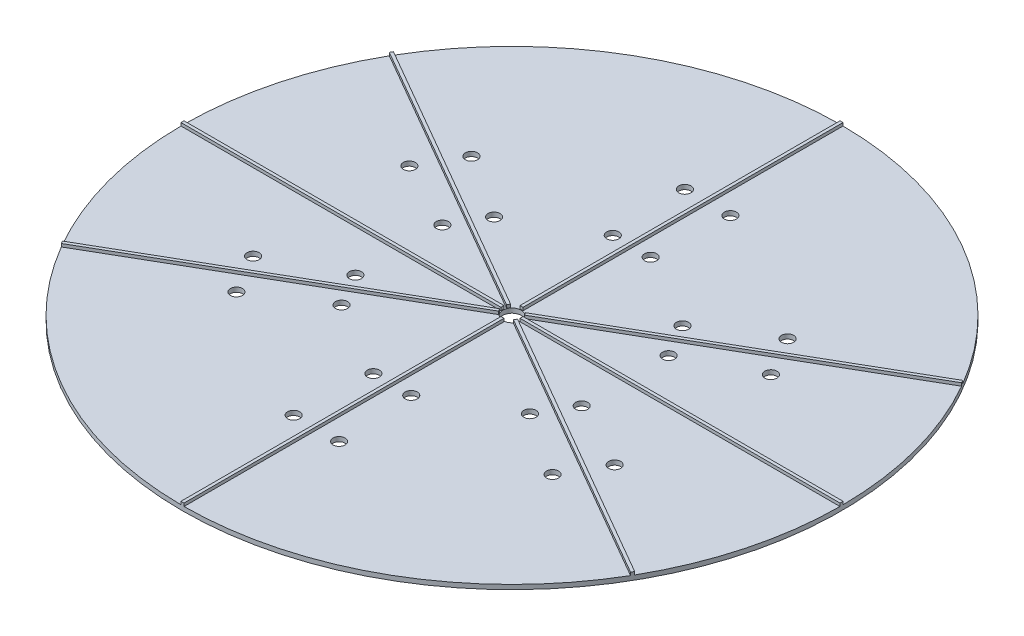
SolidWorks part; units mm, degrees
ref_plane "Front Plane" through (0, 0, 0) normal (0, 0, 1) x (1, 0, 0)
ref_plane "Top Plane" through (0, 0, 0) normal (0, 1, 0) x (1, 0, 0)
ref_plane "Right Plane" through (0, 0, 0) normal (1, 0, 0) x (0, 0, -1)
sketch "Sketch1" plane through (0, 0, 0) normal (0, 1, 0) x (1, 0, 0)
  line L0 (0, -1000) -> (0, 49000) construction
  line L1 (-1000, 0) -> (49000, 0) construction
  line L2 (0, 0) -> (-188.3605, -108.75) construction
  line L3 (0, 0) -> (188.3605, -108.75) construction
  circle A0 centre (0, 0) radius 217.5
  circle A1 centre (0, 0) radius 80 construction
  circle A2 centre (-12.5, 79.0174) radius 4
  circle A3 centre (12.5, 79.0174) radius 4
  circle A8 centre (62.1811, 50.334) radius 4
  circle A9 centre (74.6811, 28.6834) radius 4
  circle A10 centre (74.6811, -28.6834) radius 4
  circle A11 centre (62.1811, -50.334) radius 4
  circle A12 centre (12.5, -79.0174) radius 4
  circle A13 centre (-12.5, -79.0174) radius 4
  circle A14 centre (-62.1811, -50.334) radius 4
  circle A15 centre (-74.6811, -28.6834) radius 4
  circle A16 centre (-74.6811, 28.6834) radius 4
  circle A17 centre (-62.1811, 50.334) radius 4
  circle A18 centre (0, 0) radius 130 construction
  circle A19 centre (15, 129.1317) radius 4
  circle A20 centre (-15, 129.1317) radius 4
  circle A21 centre (104.3313, 77.5562) radius 4
  circle A22 centre (119.3313, 51.5755) radius 4
  circle A23 centre (119.3313, -51.5755) radius 4
  circle A24 centre (104.3313, -77.5562) radius 4
  circle A25 centre (15, -129.1317) radius 4
  circle A26 centre (-15, -129.1317) radius 4
  circle A27 centre (-104.3313, -77.5562) radius 4
  circle A28 centre (-119.3313, -51.5755) radius 4
  circle A29 centre (-119.3313, 51.5755) radius 4
  circle A30 centre (-104.3313, 77.5562) radius 4
  circle A31 centre (0, 0) radius 6
  point P24 (0, 0)
  point P37 (0, 0)
  point P64 (0, 0)
  dimension "D1" = 435
  dimension "D2" = 160
  dimension "D5" = 8
  dimension "D6" = 6
  dimension "D7" = 260
  dimension "D8" = 8
  dimension "D9" = 30
  dimension "D11" = 12
  dimension "D3" = 30
  dimension "D4" = 25
  dimension "D10" = 6
extrude "Boss-Extrude1" add sketch "Sketch1" along normal mid plane 5
sketch "Sketch2" plane through (0, 2.5, 0) normal (0, 1, 0) x (1, 0, 0)
  line L0 (-189.3776, -108.1825) -> (-188.3776, -109.9146)
  line L5 (0, 217.5) -> (0, -217.5) construction
  line L6 (-217.5, 0) -> (217.5, 0) construction
  line L7 (5.888, -2.2448) -> (189.3776, -108.1825)
  line L8 (4.888, -3.9768) -> (188.3776, -109.9146)
  line L9 (189.3776, -108.1825) -> (188.3776, -109.9146)
  line L23 (4.888, 3.9768) -> (188.3776, 109.9146)
  line L24 (189.3776, 108.1825) -> (188.3776, 109.9146)
  line L27 (5.888, 2.2448) -> (189.3776, 108.1825)
  line L28 (-5.888, 2.2448) -> (-189.3776, 108.1825)
  line L29 (-4.888, 3.9768) -> (-188.3776, 109.9146)
  line L32 (-189.3776, 108.1825) -> (-188.3776, 109.9146)
  line L34 (0, 0) -> (-108.75, 188.3605) construction
  line L35 (-1, 6.2216) -> (-1, 218.0971)
  line L37 (1, 218.0971) -> (-1, 218.0971)
  line L40 (1, 6.2216) -> (1, 218.0971)
  line L41 (6.2216, 1) -> (218.0971, 1)
  line L44 (218.0971, -1) -> (218.0971, 1)
  line L45 (-5.888, -2.2448) -> (-189.3776, -108.1825)
  line L47 (6.2216, -1) -> (218.0971, -1)
  line L50 (-4.888, -3.9768) -> (-188.3776, -109.9146)
  line L58 (1, -6.2216) -> (1, -218.0971)
  line L59 (-1, -218.0971) -> (1, -218.0971)
  line L60 (-1, -6.2216) -> (-1, -218.0971)
  line L61 (-6.2216, -1) -> (-218.0971, -1)
  line L62 (-218.0971, 1) -> (-218.0971, -1)
  line L63 (-6.2216, 1) -> (-218.0971, 1)
  arc A1 (-5.888, -2.2448) -> (-4.888, -3.9768) centre (0, 0) ccw
  circle A2 centre (0, 0) radius 217.5 construction
  arc A3 (5.888, -2.2448) -> (4.888, -3.9768) centre (0, 0) cw
  arc A4 (5.888, 2.2448) -> (4.888, 3.9768) centre (0, 0) ccw
  arc A5 (-5.888, 2.2448) -> (-4.888, 3.9768) centre (0, 0) cw
  arc A6 (1, 6.2216) -> (-1, 6.2216) centre (0, 0) ccw
  arc A7 (6.2216, -1) -> (6.2216, 1) centre (0, 0) ccw
  arc A8 (-1, -6.2216) -> (1, -6.2216) centre (0, 0) ccw
  arc A9 (-6.2216, 1) -> (-6.2216, -1) centre (0, 0) ccw
  point P0 (0, 0)
  point P13 (0, 0)
  point P17 (0, 0)
  point P31 (0, 0)
  point P47 (0, 0)
  dimension "D1" = 30
  dimension "D2" = 4
extrude "Cut-Extrude1" cut sketch "Sketch2" against normal blind 2
